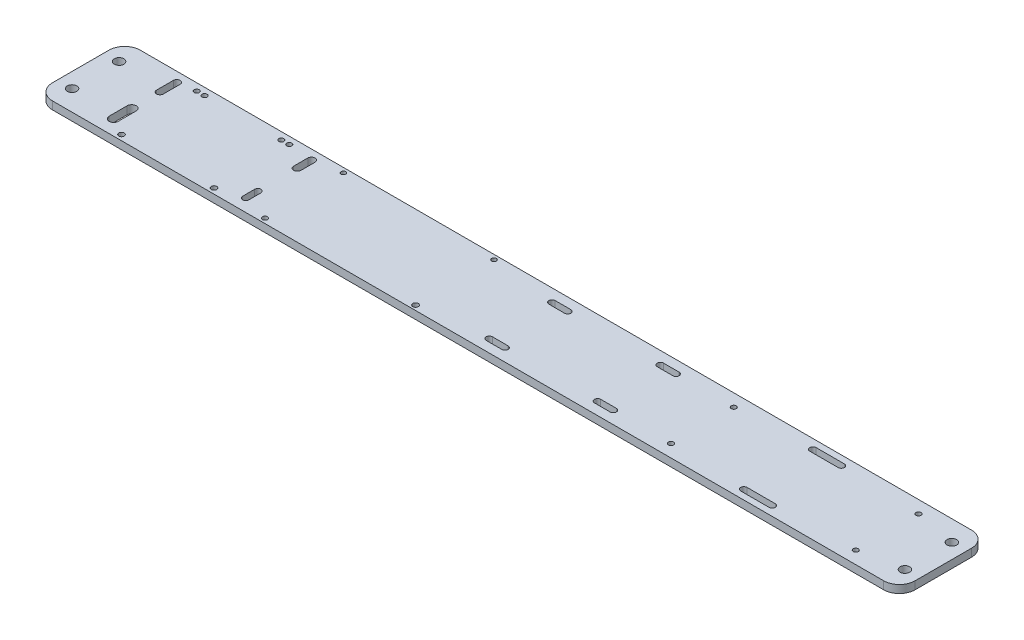
SolidWorks part; units mm, degrees
ref_plane "前视基准面" through (0, 0, 0) normal (0, 0, 1) x (1, 0, 0)
ref_plane "上视基准面" through (0, 0, 0) normal (0, 1, 0) x (1, 0, 0)
ref_plane "右视基准面" through (0, 0, 0) normal (1, 0, 0) x (0, 0, -1)
other "Configuration Table"
sketch "草图1" plane through (0, 0, 0) normal (0, 1, 0) x (1, 0, 0)
  line L0 (0, 56) -> (0, 0) construction
  line L1 (-275, 56) -> (275, 56)
  line L2 (-275, 56) -> (-275, 0)
  line L3 (-275, 0) -> (275, 0)
  line L4 (275, 56) -> (275, 0)
  line L5 (-84.4832, 65.5861) -> (-84.4832, -14.4139) construction
  line L6 (-129.4832, 65.5861) -> (-39.4832, 65.5861) construction
  line L7 (-129.4832, 65.5861) -> (-129.4832, -14.4139) construction
  line L8 (-129.4832, -14.4139) -> (-39.4832, -14.4139) construction
  line L9 (-39.4832, 65.5861) -> (-39.4832, -14.4139) construction
  line L10 (-219.3933, 51.3769) -> (-170.3933, 51.3769) construction
  line L11 (-219.3933, 51.3769) -> (-219.3933, -6.6231) construction
  line L12 (-219.3933, -6.6231) -> (-170.3933, -6.6231) construction
  line L13 (-170.3933, 51.3769) -> (-170.3933, -6.6231) construction
  line L14 (-149.7318, 49.857) -> (-149.7318, 40.8533) construction
  line L15 (-147.3975, 49.857) -> (-147.3975, 40.8533)
  line L16 (-152.0661, 49.857) -> (-152.0661, 40.8533)
  line L17 (-149.7318, 15.6761) -> (-149.7318, 8) construction
  line L18 (-147.731, 15.6761) -> (-147.731, 8)
  line L19 (-151.7327, 15.6761) -> (-151.7327, 8)
  line L20 (-235.6045, 49.857) -> (-235.6045, 39.1459) construction
  line L21 (-233.4436, 49.857) -> (-233.4436, 39.1459)
  line L22 (-237.7654, 49.857) -> (-237.7654, 39.1459)
  line L23 (-235.6045, 21.1383) -> (-235.6045, 9.6135) construction
  line L24 (-232.7233, 21.1383) -> (-232.7233, 9.6135)
  line L25 (-238.4857, 21.1383) -> (-238.4857, 9.6135)
  line L26 (15.5257, 48) -> (5.5257, 48) construction
  line L27 (15.5257, 46) -> (5.5257, 46)
  line L28 (15.5257, 50) -> (5.5257, 50)
  line L29 (84.5563, 48) -> (74.5563, 48) construction
  line L30 (84.5563, 46) -> (74.5563, 46)
  line L31 (84.5563, 50) -> (74.5563, 50)
  line L32 (15.5257, 8) -> (5.5257, 8) construction
  line L33 (15.5257, 6) -> (5.5257, 6)
  line L34 (15.5257, 10) -> (5.5257, 10)
  line L35 (84.5563, 8) -> (74.5563, 8) construction
  line L36 (84.5563, 6) -> (74.5563, 6)
  line L37 (84.5563, 10) -> (74.5563, 10)
  line L38 (169.8332, 50) -> (187.9273, 50) construction
  line L41 (169.8332, 52) -> (187.9273, 52)
  line L42 (169.8332, 48) -> (187.9273, 48)
  line L43 (169.8332, 6) -> (187.9273, 6) construction
  line L44 (169.8332, 8) -> (187.9273, 8)
  line L45 (169.8332, 4) -> (187.9273, 4)
  circle A0 centre (-265.5, 43) radius 3.05
  circle A1 centre (-265.5, 13) radius 3.05
  circle A2 centre (265.5, 13) radius 3.05
  circle A3 centre (265.5, 43) radius 3.05
  circle A4 centre (239.1766, 48) radius 1.6
  circle A5 centre (239.1766, 8) radius 1.6
  circle A6 centre (121.3766, 48) radius 1.6
  circle A7 centre (121.3766, 8) radius 1.6
  circle A8 centre (239.1766, 48) radius 3 construction
  circle A9 centre (-42.9832, 62.0861) radius 1.6 construction
  circle A10 centre (-42.9832, -10.9139) radius 1.6 construction
  circle A11 centre (-125.9832, -10.9139) radius 1.6 construction
  circle A12 centre (-125.9832, 62.0861) radius 1.6 construction
  circle A13 centre (-170.3933, 51.3769) radius 1.6
  circle A14 centre (-170.3933, -6.6231) radius 1.6 construction
  circle A15 centre (-219.3933, -6.6231) radius 1.6 construction
  circle A16 centre (-219.3933, 51.3769) radius 1.6
  circle A23 centre (-224.3933, 51.3769) radius 1.6
  circle A24 centre (-224.3933, 3.4146) radius 1.7411
  circle A25 centre (-165.3933, 51.3769) radius 1.6
  circle A26 centre (-165.3933, 3.4146) radius 1.7411
  circle A27 centre (-132.4832, 53) radius 1.4697
  circle A28 centre (-132.4832, 3) radius 1.6198
  circle A29 centre (-36.4832, 53) radius 1.4944
  circle A30 centre (-36.4832, 3) radius 1.7807
  arc A31 (-147.3975, 49.857) -> (-152.0661, 49.857) centre (-149.7318, 49.857) ccw
  arc A32 (-152.0661, 40.8533) -> (-147.3975, 40.8533) centre (-149.7318, 40.8533) ccw
  arc A33 (-147.731, 15.6761) -> (-151.7327, 15.6761) centre (-149.7318, 15.6761) ccw
  arc A34 (-151.7327, 8) -> (-147.731, 8) centre (-149.7318, 8) ccw
  arc A35 (-233.4436, 49.857) -> (-237.7654, 49.857) centre (-235.6045, 49.857) ccw
  arc A36 (-237.7654, 39.1459) -> (-233.4436, 39.1459) centre (-235.6045, 39.1459) ccw
  arc A37 (-232.7233, 21.1383) -> (-238.4857, 21.1383) centre (-235.6045, 21.1383) ccw
  arc A38 (-238.4857, 9.6135) -> (-232.7233, 9.6135) centre (-235.6045, 9.6135) ccw
  arc A39 (15.5257, 46) -> (15.5257, 50) centre (15.5257, 48) ccw
  arc A40 (5.5257, 50) -> (5.5257, 46) centre (5.5257, 48) ccw
  arc A41 (84.5563, 46) -> (84.5563, 50) centre (84.5563, 48) ccw
  arc A42 (74.5563, 50) -> (74.5563, 46) centre (74.5563, 48) ccw
  arc A43 (15.5257, 6) -> (15.5257, 10) centre (15.5257, 8) ccw
  arc A44 (5.5257, 10) -> (5.5257, 6) centre (5.5257, 8) ccw
  arc A45 (84.5563, 6) -> (84.5563, 10) centre (84.5563, 8) ccw
  arc A46 (74.5563, 10) -> (74.5563, 6) centre (74.5563, 8) ccw
  arc A49 (169.8332, 52) -> (169.8332, 48) centre (169.8332, 50) ccw
  arc A50 (187.9273, 48) -> (187.9273, 52) centre (187.9273, 50) ccw
  arc A51 (169.8332, 8) -> (169.8332, 4) centre (169.8332, 6) ccw
  arc A52 (187.9273, 4) -> (187.9273, 8) centre (187.9273, 6) ccw
  point P4 (0, 0)
  point P33 (-149.7318, 45.3552)
  point P69 (-149.7318, 11.838)
  point P77 (-235.6045, 44.5015)
  point P86 (-235.6045, 15.3759)
  point P93 (10.5257, 48)
  point P100 (79.5563, 48)
  point P107 (10.5257, 8)
  point P114 (79.5563, 8)
  point P123 (178.8802, 50)
  point P128 (178.8802, 6)
  point P135 (0, 0)
  point P136 (188.8475, 7.4192)
  point P137 (180.6915, 5.3047)
  point P138 (0, 0)
  dimension "D1" = 6.1
  dimension "D2" = 30
  dimension "D6" = 13
  dimension "D7" = 3.2
  dimension "D8" = 6
  dimension "D10" = 8
  dimension "D16" = 3.2
  dimension "D21" = 3.2
  dimension "D28" = 6
  dimension "D3" = 5
  dimension "D22" = 5
  dimension "D23" = 3
  dimension "D24" = 3
  dimension "D26" = 3
  dimension "D27" = 10
  dimension "D29" = 2
  dimension "D31" = 550
  dimension "D4" = 265.5
  dimension "D5" = 56
  dimension "D9" = 117.8
  dimension "40" = 40
  dimension "D11" = 90
  dimension "D12" = 80
  dimension "D13" = 3.5
  dimension "D14" = 3.5
  dimension "D15" = 7
  dimension "D17" = 7
  dimension "D18" = 7
  dimension "D19" = 58
  dimension "D20" = 49
  dimension "D25" = 3
  dimension "D30" = 6
extrude "凸台-拉伸1" add sketch "草图1" along normal blind 5
fillet "圆角1" radius 10 4 edges at (275, 2.5, -56) (275, 2.5, 0) (-275, 2.5, 0) (-275, 2.5, -56)
